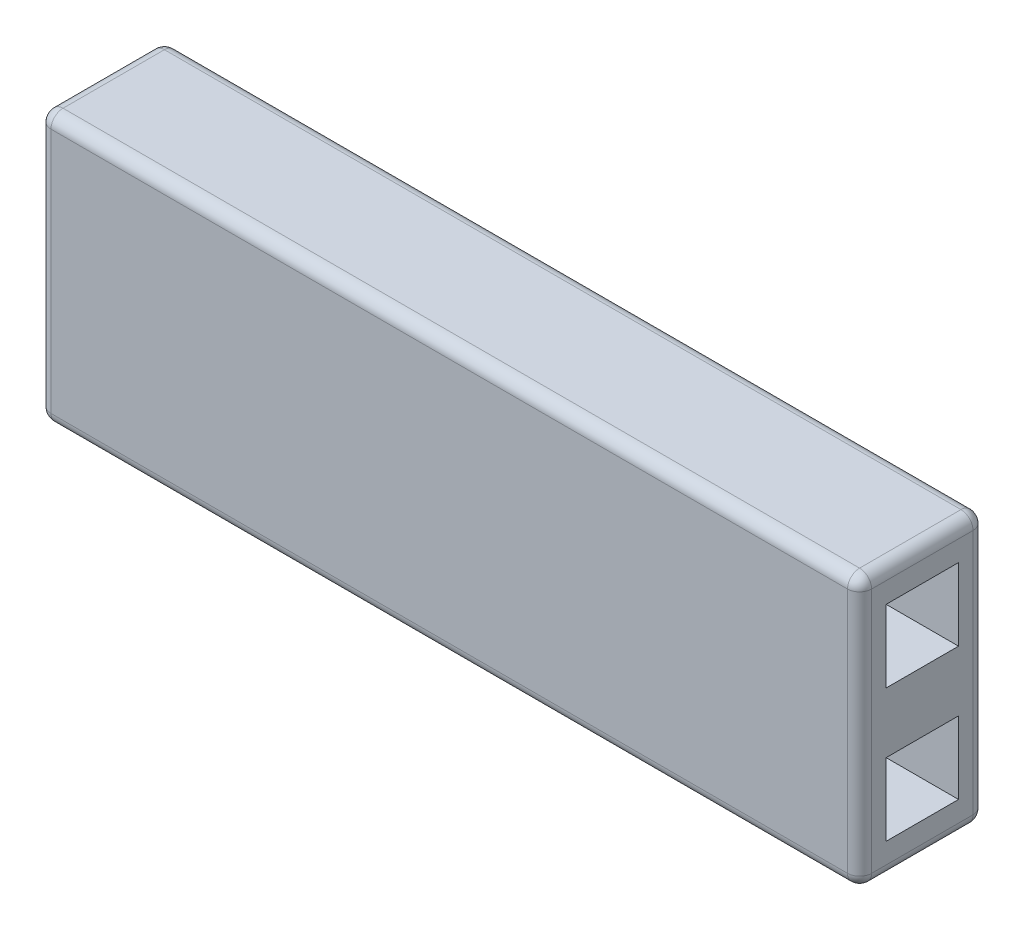
SolidWorks part; units mm, degrees
ref_plane "Alzado" through (0, 0, 0) normal (1, 0, 0) x (0, 1, 0)
ref_plane "Planta" through (0, 0, 0) normal (0, 0, 1) x (0, 1, 0)
ref_plane "Vista lateral" through (0, 0, 0) normal (0, 1, 0) x (-1, 0, 0)
sketch "Croquis1" plane through (0, 0, 0) normal (1, 0, 0) x (0, 1, 0)
  line L1 (-2.8, -1.3) -> (2.8, -1.3)
  line L2 (-2.8, -1.3) -> (-2.8, 1.3)
  line L3 (-2.8, 1.3) -> (2.8, 1.3)
  line L4 (2.8, -1.3) -> (2.8, 1.3)
  line L5 (-2.8, -1.3) -> (2.8, 1.3) construction
  line L6 (-2.8, 1.3) -> (2.8, -1.3) construction
  point P0 (0, 0)
  dimension "D1" = 2.6
  dimension "D2" = 5.6
extrude "Saliente-Extruir1" add sketch "Croquis1" along normal blind 17
sketch "Croquis2" plane through (17, 0, 0) normal (1, 0, 0) x (0, 1, 0)
  line L0 (0, -1.43) -> (0, 1.43) construction
  line L5 (0.625, 0.75) -> (2.125, 0.75)
  line L6 (0.625, 0.75) -> (0.625, -0.75)
  line L7 (0.625, -0.75) -> (2.125, -0.75)
  line L8 (2.125, 0.75) -> (2.125, -0.75)
  line L9 (-0.625, -0.75) -> (-2.125, -0.75)
  line L10 (-2.125, 0.75) -> (-2.125, -0.75)
  line L11 (-0.625, 0.75) -> (-2.125, 0.75)
  line L12 (-0.625, 0.75) -> (-0.625, -0.75)
  point P0 (0.625, 0)
  point P1 (0, 0)
  dimension "D1" = 1.5
  dimension "D2" = 1.5
  dimension "D3" = 1.25
extrude "Cortar-Extruir1" cut sketch "Croquis2" against normal blind 3
fillet "Redondeo1" radius 0.25 12 edges at (17, 2.8, 0) (0, 2.8, 0) (17, -2.8, 0) (0, -2.8, 0) (8.5, 2.8, 1.3) (17, 0, 1.3) (8.5, -2.8, 1.3) (0, 0, 1.3) (8.5, -2.8, -1.3) (17, 0, -1.3) (8.5, 2.8, -1.3) (0, 0, -1.3)
